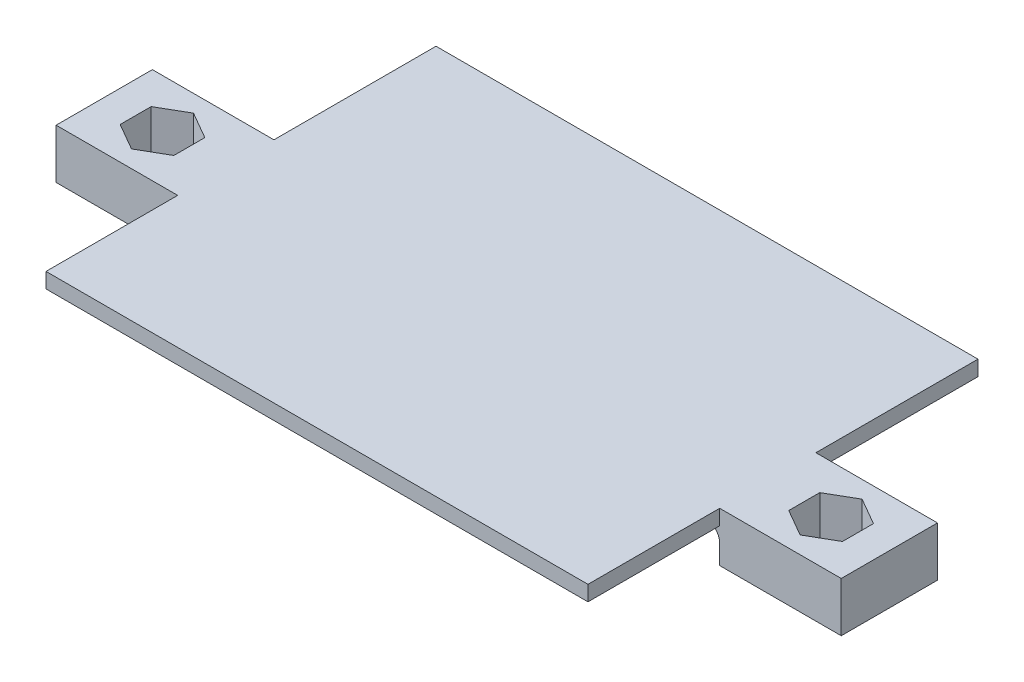
SolidWorks part; units mm, degrees
ref_plane "Front Plane" through (0, 0, 0) normal (0, 0, 1) x (1, 0, 0)
ref_plane "Top Plane" through (0, 0, 0) normal (0, 1, 0) x (1, 0, 0)
ref_plane "Right Plane" through (0, 0, 0) normal (1, 0, 0) x (0, 0, -1)
sketch "Sketch1" plane through (0, 0, 0) normal (0, 1, 0) x (1, 0, 0)
  line L1 (26.75, 19.25) -> (-26.75, 19.25)
  line L2 (26.75, 19.25) -> (26.75, -19.25)
  line L3 (26.75, -19.25) -> (-26.75, -19.25)
  line L4 (-26.75, 19.25) -> (-26.75, -19.25)
  line L5 (26.75, 19.25) -> (-26.75, -19.25) construction
  line L6 (26.75, -19.25) -> (-26.75, 19.25) construction
  line L7 (-27, -19.5) -> (27, -19.5)
  line L8 (-27, -19.5) -> (-27, 19.5)
  line L9 (-27, 19.5) -> (27, 19.5)
  line L10 (27, -19.5) -> (27, 19.5)
  line L11 (-27, -19.5) -> (27, 19.5) construction
  line L12 (-27, 19.5) -> (27, -19.5) construction
  point P0 (0, 0)
  point P6 (0, 0)
  dimension "D1" = 53.5
  dimension "D2" = 38.5
  dimension "D3" = 54
  dimension "D4" = 39
extrude "Boss-Extrude1" add sketch "Sketch1" against normal blind 1.5 contours L4 L3 L2 L1
sketch "Sketch2" plane through (0, 0, 0) normal (0, 1, 0) x (1, 0, 0)
  line L0 (-27, -19.5) -> (-27, -6.5) construction
  line L5 (27, 19.5) -> (-27, -19.5) construction
  line L6 (27, -19.5) -> (-27, 19.5) construction
  line L7 (-27, -6.5) -> (-39, -6.5) construction
  line L8 (-39, -6.5) -> (-39, 3.5) construction
  line L9 (-39, 3.5) -> (-27, 3.5) construction
  line L10 (0, 19.25) -> (0, -19.25) construction
  line L11 (-38.75, -6.25) -> (-26.75, -6.25)
  line L12 (-33, -4.56) -> (-30.35, -3.03)
  line L13 (-30.35, -3.03) -> (-30.35, 0.03)
  line L14 (-30.35, 0.03) -> (-33, 1.56)
  line L15 (-33, 1.56) -> (-35.65, 0.03)
  line L16 (-35.65, 0.03) -> (-35.65, -3.03)
  line L17 (-35.65, -3.03) -> (-33, -4.56)
  line L18 (-38.75, -6.25) -> (-38.75, 3.25)
  line L19 (-38.75, 3.25) -> (-26.75, 3.25)
  line L20 (-26.75, 3.25) -> (-26.75, -6.25)
  line L21 (-26.75, 19.25) -> (-26.75, -19.25) construction
  line L22 (26.75, 19.25) -> (-26.75, 19.25) construction
  line L23 (26.75, -19.25) -> (-26.75, -19.25) construction
  line L24 (-26.75, 19.25) -> (-26.75, 3.25) construction
  line L25 (26.75, 19.25) -> (-26.75, 19.25) construction
  line L26 (26.75, -19.25) -> (-27, -19.25) construction
  line L27 (26.75, 19.25) -> (26.75, -19.25) construction
  line L28 (-27, -6.25) -> (-38.75, -6.25) construction
  line L29 (-27, 19.5) -> (-27, 3.5) construction
  line L30 (27, 19.5) -> (-27, 19.5) construction
  line L31 (27, 19.5) -> (27, -19.5) construction
  line L32 (27, -19.5) -> (-27, -19.5) construction
  line L33 (38.75, -6.25) -> (38.75, 3.25)
  line L34 (38.75, 3.25) -> (26.75, 3.25)
  line L35 (26.75, 3.25) -> (26.75, -6.25)
  line L36 (38.75, -6.25) -> (26.75, -6.25)
  line L37 (35.65, -3.03) -> (33, -4.56)
  line L38 (35.65, 0.03) -> (35.65, -3.03)
  line L39 (33, 1.56) -> (35.65, 0.03)
  line L40 (30.35, 0.03) -> (33, 1.56)
  line L41 (30.35, -3.03) -> (30.35, 0.03)
  line L42 (33, -4.56) -> (30.35, -3.03)
  circle A0 centre (-33, -1.5) radius 2.65 construction
  circle A1 centre (33, -1.5) radius 2.65 construction
  point P0 (0, 0)
  dimension "D4" = 5
  dimension "D6" = 5.3
  dimension "D1" = 54
  dimension "D2" = 39
  dimension "D3" = 13
  dimension "D5" = 6
  dimension "D7" = 0.25
extrude "Boss-Extrude2" add sketch "Sketch2" against normal blind 4.9
fillet "Fillet1" radius 1.5 2 edges at (-26.75, -1.5, 1.5) (26.75, -1.5, 1.5)
